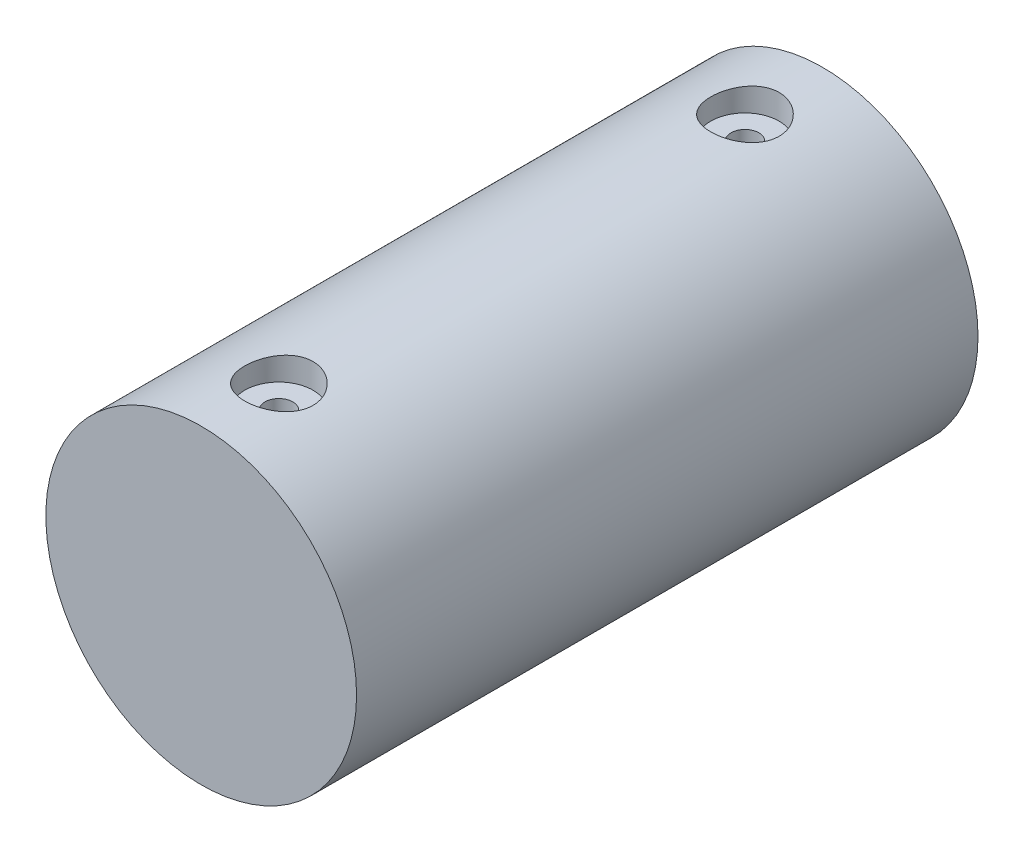
SolidWorks part; units mm, degrees
ref_plane "Ebene vorne" through (0, 0, 0) normal (0, 0, 1) x (1, 0, 0)
ref_plane "Ebene oben" through (0, 0, 0) normal (0, 1, 0) x (1, 0, 0)
ref_plane "Ebene rechts" through (0, 0, 0) normal (1, 0, 0) x (0, 0, -1)
sketch "Skizze1" plane through (0, 0, 0) normal (0, 0, 1) x (1, 0, 0)
  circle A0 centre (0, 0) radius 50
  dimension "D1" = 100
extrude "Aufsatz-Linear austragen1" add sketch "Skizze1" along normal blind 200
ref_plane "Ebene1" through (0, 50, 0) normal (0, 1, 0) x (1, 0, 0)
hole_wizard "Stirnsenkung für M8 Senkschraube (Kopf Button)1" positions "Skizze3" profile "Skizze2" counterbore size "M8" standard "ANSI Metrisch" end condition through all
sketch "Skizze3" plane through (0, 50, 0) normal (0, 1, 0) x (1, 0, 0)
  line L0 (-50, -200) -> (50, -200) construction
  point P0 (0, -25)
  point P2 (0, -175)
  dimension "D1" = 150
  dimension "D2" = 25
sketch "Skizze2" plane through (0, 50, 25) normal (1, 0, 0) x (0, 0, 1)
  line L0 (0, 0) -> (0, 100)
  line L1 (0, 100) -> (4.5, 100)
  line L3 (4.5, 100) -> (4.5, 8)
  line L4 (4.5, 8) -> (11, 8)
  line L5 (11, 8) -> (11, 0)
  line L7 (11, 0) -> (0, 0)
  line L11 (0, -6.35) -> (0, 107.95) construction
  dimension "Bohrerdurchmesser" = 9
  dimension "Bohrungstiefe" = 100
  dimension "Senkdurchmesser2" = 22
  dimension "Senktiefe2" = 8
ref_plane "Ebene2" through (0, -50, 0) normal (0, -1, 0) x (-1, 0, 0)
hole_wizard "Stirnsenkung für M8 Senkschraube (Kopf Button)2" positions "Skizze6" profile "Skizze5" counterbore size "M8" standard "ANSI Metrisch" end condition through all
sketch "Skizze6" plane through (0, -50, 0) normal (0, -1, 0) x (-1, 0, 0)
  point P0 (0, -175)
  point P3 (0, -25)
sketch "Skizze5" plane through (0, -50, 175) normal (1, 0, 0) x (0, 0, -1)
  line L0 (0, 0) -> (0, 100)
  line L1 (0, 100) -> (4.5, 100)
  line L3 (4.5, 100) -> (4.5, 8)
  line L4 (4.5, 8) -> (7.5, 8)
  line L5 (7.5, 8) -> (7.5, 0)
  line L7 (7.5, 0) -> (0, 0)
  line L11 (0, -6.35) -> (0, 107.95) construction
  dimension "Bohrerdurchmesser" = 9
  dimension "Bohrungstiefe" = 100
  dimension "Senkdurchmesser2" = 15
  dimension "Senktiefe2" = 8
